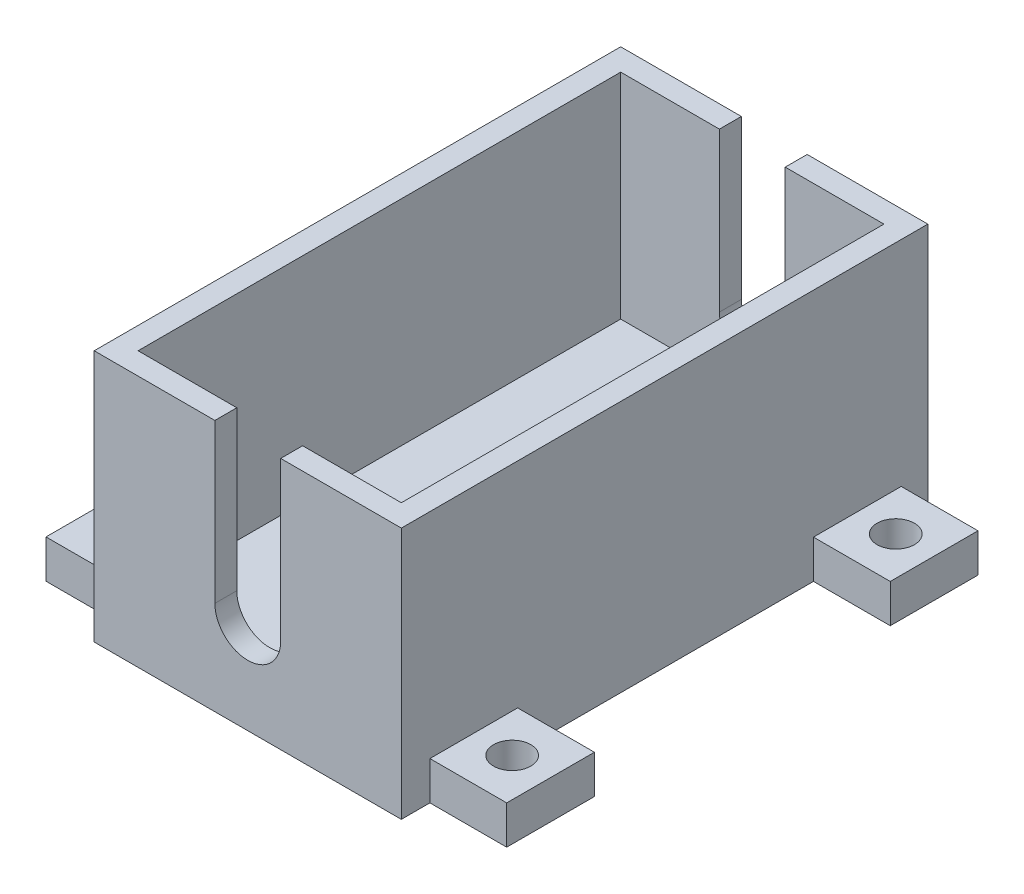
SolidWorks part; units mm, degrees
ref_plane "Front Plane" through (0, 0, 0) normal (0, 0, 1) x (1, 0, 0)
ref_plane "Top Plane" through (0, 0, 0) normal (0, 1, 0) x (1, 0, 0)
ref_plane "Right Plane" through (0, 0, 0) normal (1, 0, 0) x (0, 0, -1)
sketch "Sketch1" plane through (0, 0, 0) normal (0, 1, 0) x (1, 0, 0)
  line L1 (-11, 21) -> (11, 21) construction
  line L2 (-11, 21) -> (-11, -21) construction
  line L3 (-11, -21) -> (11, -21) construction
  line L4 (11, 21) -> (11, -21) construction
  line L5 (-11, 21) -> (11, -21) construction
  line L6 (-11, -21) -> (11, 21) construction
  line L7 (-14, 24) -> (14, 24)
  line L8 (-14, 24) -> (-14, -24)
  line L9 (-14, -24) -> (14, -24)
  line L10 (14, 24) -> (14, -24)
  line L11 (-14, 24) -> (14, -24) construction
  line L12 (-14, -24) -> (14, 24) construction
  point P0 (0, 0)
  point P6 (0, 0)
  dimension "D1" = 42
  dimension "D2" = 22
  dimension "D3" = 3
  dimension "D5" = 3
extrude "Boss-Extrude1" add sketch "Sketch1" along normal blind 23
sketch "Sketch3" plane through (0, 23, 0) normal (0, 1, 0) x (1, 0, 0)
  line L1 (-12, 22) -> (12, 22)
  line L2 (-12, 22) -> (-12, -22)
  line L3 (-12, -22) -> (12, -22)
  line L4 (12, 22) -> (12, -22)
  line L5 (-12, 22) -> (12, -22) construction
  line L6 (-12, -22) -> (12, 22) construction
  point P0 (0, 0)
  dimension "D1" = 44
  dimension "D2" = 24
extrude "Cut-Extrude1" cut sketch "Sketch3" against normal blind 19.5
sketch "Sketch4" plane through (0, 0, 0) normal (0, -1, 0) x (1, 0, 0)
  line L0 (14, 21.3952) -> (21, 21.3952)
  line L1 (14, 24) -> (14, -24) construction
  line L2 (21, 21.3952) -> (21, 13.3952)
  line L3 (21, 13.3952) -> (14, 13.3952)
  line L4 (14, 13.3952) -> (14, 21.3952)
  line L5 (14, -13.5742) -> (21, -13.5742)
  line L6 (21, -13.5742) -> (21, -21.5742)
  line L7 (21, -21.5742) -> (14, -21.5742)
  line L8 (14, -21.5742) -> (14, -13.5742)
  line L9 (-14, -21.5742) -> (-21, -21.5742)
  line L10 (-14, -24) -> (-14, 24) construction
  line L11 (-21, -21.5742) -> (-21, -13.5742)
  line L12 (-21, -13.5742) -> (-14, -13.5742)
  line L13 (-14, -13.5742) -> (-14, -21.5742)
  line L14 (-14, 13.3952) -> (-21, 13.3952)
  line L15 (-21, 13.3952) -> (-21, 21.3952)
  line L16 (-21, 21.3952) -> (-14, 21.3952)
  line L17 (-14, 21.3952) -> (-14, 13.3952)
  line L18 (-21, 17.3952) -> (-14, 17.3952) construction
  line L19 (-21, -17.5742) -> (-14, -17.5742) construction
  circle A0 centre (17.4118, 17.4354) radius 1.7 construction
  circle A1 centre (17.4118, -17.5646) radius 1.7 construction
  circle A2 centre (-17.5882, -17.5645) radius 1.7 construction
  circle A3 centre (-17.5882, 17.4355) radius 1.7 construction
  dimension "D2" = 3.4
  dimension "D3" = 3.4
  dimension "D4" = 3.4
  dimension "D5" = 3.4
  dimension "D1" = 35
  dimension "D6" = 35
  dimension "D7" = 35
  dimension "D8" = 35
  dimension "D9" = 8
  dimension "D10" = 7
  dimension "D11" = 7
  dimension "D12" = 8
  dimension "D13" = 8
  dimension "D14" = 7
  dimension "D15" = 7
  dimension "D16" = 8
  dimension "D17" = 26.9694
extrude "Boss-Extrude2" add sketch "Sketch4" against normal blind 3.5
sketch "Sketch5" plane through (0, 0, 0) normal (0, -1, 0) x (1, 0, 0)
  line L0 (-21, 17.3952) -> (24.2445, 17.3952) construction
  line L1 (-21, 21.3952) -> (-21, 13.3952) construction
  line L2 (-21, -17.5742) -> (24.2445, -17.5742) construction
  line L3 (-21, -13.5742) -> (-21, -21.5742) construction
  line L4 (-17.5, -21.5742) -> (-17.5, 24.8845) construction
  line L5 (-21, -21.5742) -> (-14, -21.5742) construction
  line L6 (17.5, 21.3952) -> (17.5, -24.0968) construction
  line L7 (21, 21.3952) -> (14, 21.3952) construction
  circle A0 centre (-17.5, 17.3952) radius 1.7
  circle A1 centre (-17.5, -17.5742) radius 1.7
  circle A2 centre (17.5, -17.5742) radius 1.7
  circle A3 centre (17.5, 17.3952) radius 1.7
  dimension "D1" = 3.4
  dimension "D2" = 3.4
  dimension "D3" = 3.4
  dimension "D4" = 3.4
extrude "Cut-Extrude5" cut sketch "Sketch5" against normal blind 3.5
sketch "Sketch7" plane through (0, 0, 24) normal (0, 0, 1) x (1, 0, 0)
  line L0 (0, 25.9621) -> (0, 8.5568) construction
  line L1 (3, 25.9621) -> (3, 8.5568)
  line L2 (-3, 25.9621) -> (-3, 8.5568)
  arc A0 (3, 25.9621) -> (-3, 25.9621) centre (0, 25.9621) ccw
  arc A1 (-3, 8.5568) -> (3, 8.5568) centre (0, 8.5568) ccw
  point P3 (0, 17.2594)
  point P8 (0, 6.743)
  point P9 (0, 5.7338)
  point P10 (0, 7.8161)
  point P11 (0, 8.5568)
  dimension "D1" = 6
extrude "Cut-Extrude7" cut sketch "Sketch7" against normal blind 50
equation "\"3mmm\"=10"
